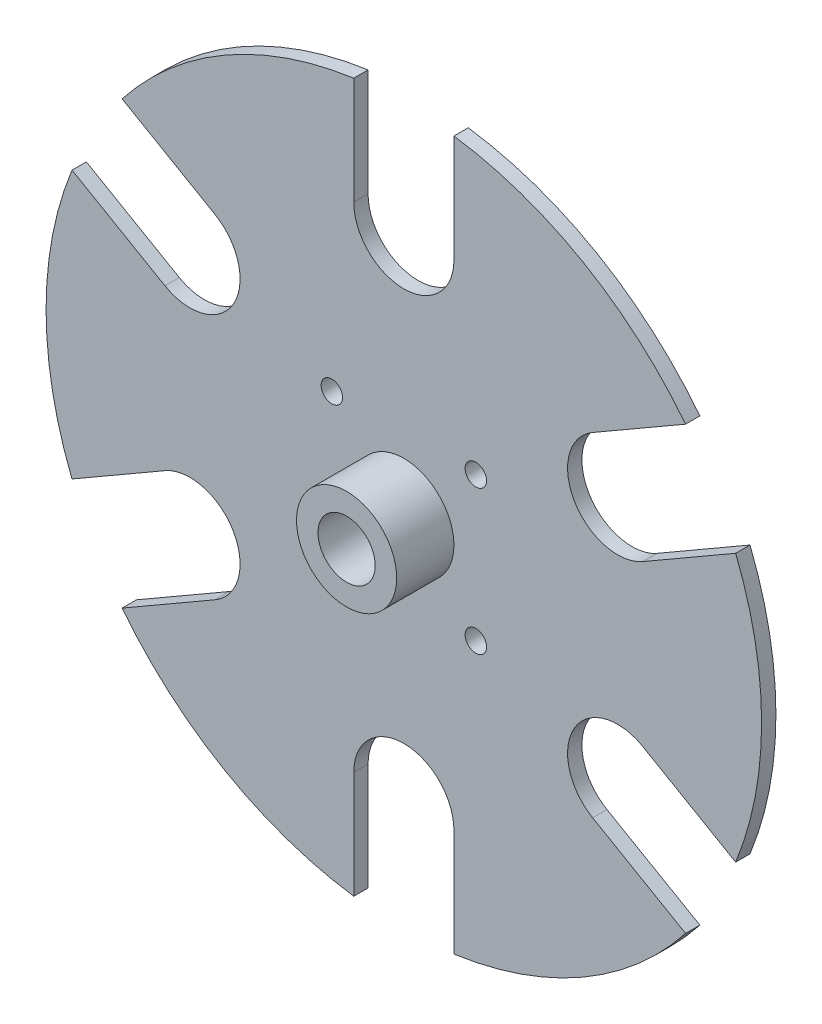
SolidWorks part; units mm, degrees
ref_plane "Front Plane" through (0, 0, 0) normal (0, 0, 1) x (1, 0, 0)
ref_plane "Top Plane" through (0, 0, 0) normal (0, 1, 0) x (1, 0, 0)
ref_plane "Right Plane" through (0, 0, 0) normal (1, 0, 0) x (0, 0, -1)
sketch "Sketch1" plane through (0, 0, 0) normal (0, 0, 1) x (1, 0, 0)
  line L0 (0, 0) -> (0, 22.0431) construction
  line L1 (0, 22.0431) -> (0, -27.0486) construction
  line L2 (0, -27.0486) -> (0, -2.5028) construction
  line L3 (0, 0) -> (34.3402, 0) construction
  line L4 (34.3402, 0) -> (-48.5021, 0) construction
  line L5 (0, 0) -> (-22.0431, 22.0431) construction
  circle A0 centre (0, 0) radius 4
  circle A1 centre (0, 0) radius 20
  circle A2 centre (-10.062, 10.062) radius 1.5
  circle A3 centre (10.062, 10.062) radius 1.5
  circle A4 centre (10.062, -10.062) radius 1.5
  circle A5 centre (-10.062, -10.062) radius 1.5
  dimension "D1" = 8
  dimension "D2" = 40
  dimension "D3" = 3
extrude "Boss-Extrude1" add sketch "Sketch1" along normal blind 5
sketch "Sketch2" plane through (0, 0, 5) normal (0, 0, 1) x (1, 0, 0)
  circle A0 centre (0, 0) radius 4
  circle A1 centre (0, 0) radius 7
  dimension "D2" = 8
  dimension "D1" = 3
extrude "Boss-Extrude2" add sketch "Sketch2" along normal blind 10
sketch "Sketch3" plane through (0, 0, 5) normal (0, 0, 1) x (1, 0, 0)
  circle A0 centre (0, 0) radius 50
  circle A1 centre (0, 0) radius 4
  dimension "D1" = 100
extrude "Boss-Extrude3" add sketch "Sketch3" along normal blind 2
sketch "Sketch4" plane through (0, 0, 7) normal (0, 0, 1) x (1, 0, 0)
  line L0 (0, 0) -> (0, 27.5076) construction
  line L1 (-7, 49.5076) -> (-7, 34.5076)
  line L2 (39.3748, 30.816) -> (26.3844, 23.316)
  line L3 (7, 49.5076) -> (7, 34.5076)
  line L4 (0, 49.5076) -> (0, 50) construction
  line L5 (46.3748, 18.6916) -> (33.3844, 11.1916)
  line L6 (46.3748, -18.6916) -> (33.3844, -11.1916)
  line L7 (39.3748, -30.816) -> (26.3844, -23.316)
  line L8 (7, -49.5076) -> (7, -34.5076)
  line L9 (-7, -49.5076) -> (-7, -34.5076)
  line L10 (-39.3748, -30.816) -> (-26.3844, -23.316)
  line L11 (-46.3748, -18.6916) -> (-33.3844, -11.1916)
  line L12 (-46.3748, 18.6916) -> (-33.3844, 11.1916)
  line L13 (-39.3748, 30.816) -> (-26.3844, 23.316)
  circle A0 centre (0, 0) radius 50 construction
  arc A1 (7, 49.5076) -> (-7, 49.5076) centre (0, 0) ccw
  arc A2 (-7, 34.5076) -> (7, 34.5076) centre (0, 34.5076) ccw
  arc A3 (26.3844, 23.316) -> (33.3844, 11.1916) centre (29.8844, 17.2538) ccw
  arc A4 (46.3748, 18.6916) -> (39.3748, 30.816) centre (0, 0) ccw
  arc A5 (33.3844, -11.1916) -> (26.3844, -23.316) centre (29.8844, -17.2538) ccw
  arc A6 (39.3748, -30.816) -> (46.3748, -18.6916) centre (0, 0) ccw
  arc A7 (7, -34.5076) -> (-7, -34.5076) centre (0, -34.5076) ccw
  arc A8 (-7, -49.5076) -> (7, -49.5076) centre (0, 0) ccw
  arc A9 (-26.3844, -23.316) -> (-33.3844, -11.1916) centre (-29.8844, -17.2538) ccw
  arc A10 (-46.3748, -18.6916) -> (-39.3748, -30.816) centre (0, 0) ccw
  arc A11 (-33.3844, 11.1916) -> (-26.3844, 23.316) centre (-29.8844, 17.2538) ccw
  arc A12 (-39.3748, 30.816) -> (-46.3748, 18.6916) centre (0, 0) ccw
  point P11 (0, 34.5076)
  point P42 (0, 0)
  dimension "D1" = 7
  dimension "D2" = 15
  dimension "D3" = 6
extrude "Cut-Extrude1" cut sketch "Sketch4" against normal blind 2
sketch "Sketch5" plane through (0, 0, 0) normal (0, 0, -1) x (-1, 0, 0)
  circle A0 centre (-10.062, 10.062) radius 1.5
  circle A1 centre (-10.062, -10.062) radius 1.5
  circle A2 centre (10.062, 10.062) radius 1.5
  circle A3 centre (10.062, -10.062) radius 1.5
extrude "Cut-Extrude2" cut sketch "Sketch5" against normal through all both and the other way through all
